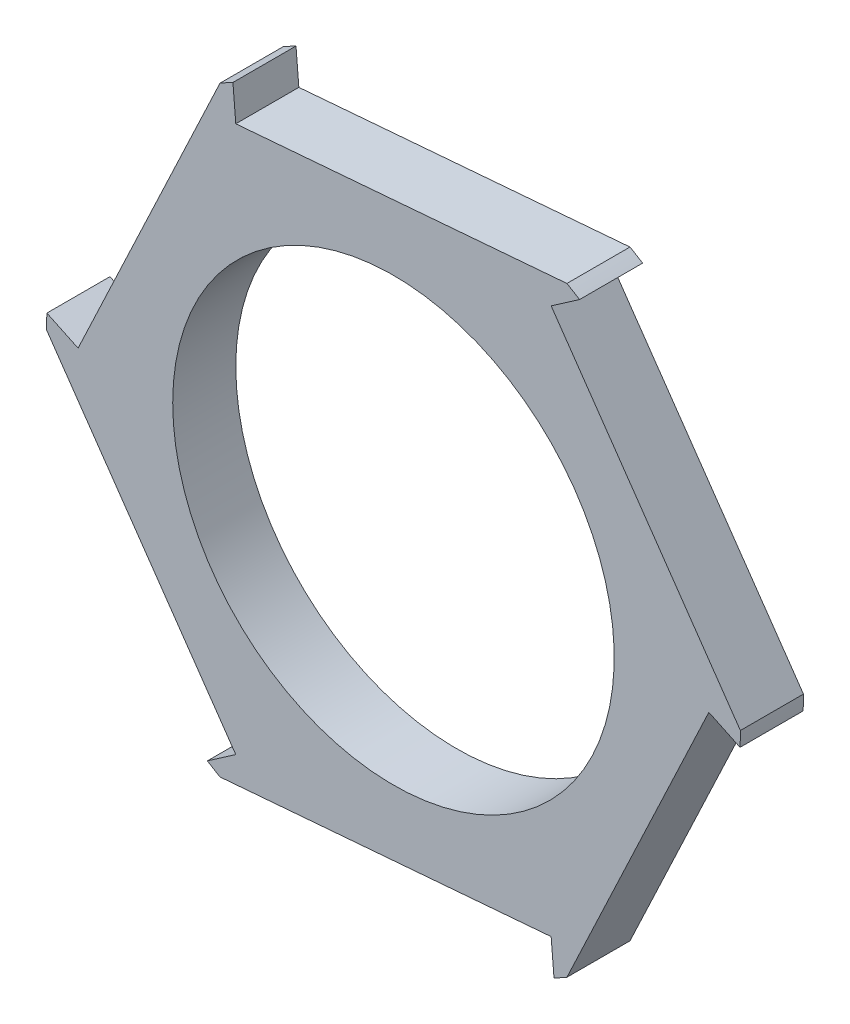
SolidWorks part; units mm, degrees
ref_plane "Front Plane" through (0, 0, 0) normal (0, 0, 1) x (1, 0, 0)
ref_plane "Top Plane" through (0, 0, 0) normal (0, 1, 0) x (1, 0, 0)
ref_plane "Right Plane" through (0, 0, 0) normal (1, 0, 0) x (0, 0, -1)
sketch "Sketch4" plane through (0, 0, 0) normal (0, 0, 1) x (1, 0, 0)
  line L0 (-50, 86.6025) -> (-55, 95.2628)
  line L1 (100, 0) -> (50, 86.6025)
  line L2 (50, 86.6025) -> (-50, 86.6025)
  line L3 (-50, 86.6025) -> (-100, 0)
  line L4 (-100, 0) -> (-50, -86.6025)
  line L5 (-50, -86.6025) -> (50, -86.6025)
  line L6 (50, -86.6025) -> (100, 0)
  line L7 (50, 86.6025) -> (55, 95.2628)
  line L8 (100, 0) -> (110, 0)
  line L9 (50, -86.6025) -> (55, -95.2628)
  line L10 (-50, -86.6025) -> (-55, -95.2628)
  line L11 (-100, 0) -> (-110, 0)
  line L12 (-50, 86.6025) -> (-55, 95.2628)
  line L13 (-100, 0) -> (-55, 95.2628)
  line L14 (-50, 86.6025) -> (55, 95.2628)
  line L15 (50, 86.6025) -> (110, 0)
  line L16 (100, 0) -> (55, -95.2628)
  line L17 (50, -86.6025) -> (-55, -95.2628)
  line L18 (-50, -86.6025) -> (-110, 0)
  line L19 (-50, 86.6025) -> (-50.9, 97.5151)
  line L20 (50, 86.6025) -> (59.0005, 92.8383)
  line L21 (100, 0) -> (109.9005, -4.6768)
  line L22 (50, -86.6025) -> (50.9, -97.5151)
  line L23 (-50, -86.6025) -> (-59.0005, -92.8383)
  line L24 (-100, 0) -> (-109.9005, 4.6768)
  circle A0 centre (0, 0) radius 100 construction
  circle A1 centre (0, 0) radius 110
  point P23 (0, 0)
  point P33 (0, 0)
  point P37 (0, 0)
  point P39 (0, 0)
  dimension "D1" = 10
  dimension "D2" = 10
  dimension "D4" = 90
  dimension "D3" = 6
  dimension "D5" = 6
  dimension "D6" = 6
  dimension "D7" = 10.9496
extrude "Boss-Extrude1" add sketch "Sketch4" along normal blind 20 contours L5 L6 L1 L2 L3 L4 | L18 L4 L11 | L13 L3 L0 | L14 L2 L7 | L15 L1 L8 | L16 L6 L9 | L17 L5 L10 | L19 A1 L0 | L20 A1 L7 | L21 A1 L8 | L22 A1 L9 | L23 A1 L10 | L24 A1 L11
sketch "Sketch6" plane through (-42.5676, -3.5109, 0) normal (0.9966, 0.0822, 0) x (0, 0, -1)
  line L0 (-20, 101.369) -> (0, 101.369) construction
  circle A0 centre (-10, 101.369) radius 5
  point P4 (0, 0)
  dimension "D1" = 10
sketch "Sketch7" plane through (0, 0, 0) normal (0, 0, -1) x (-1, 0, 0)
  circle A0 centre (0, 0) radius 70
  dimension "D1" = 140
extrude "Cut-Extrude1" cut sketch "Sketch7" against normal through all contours A0
